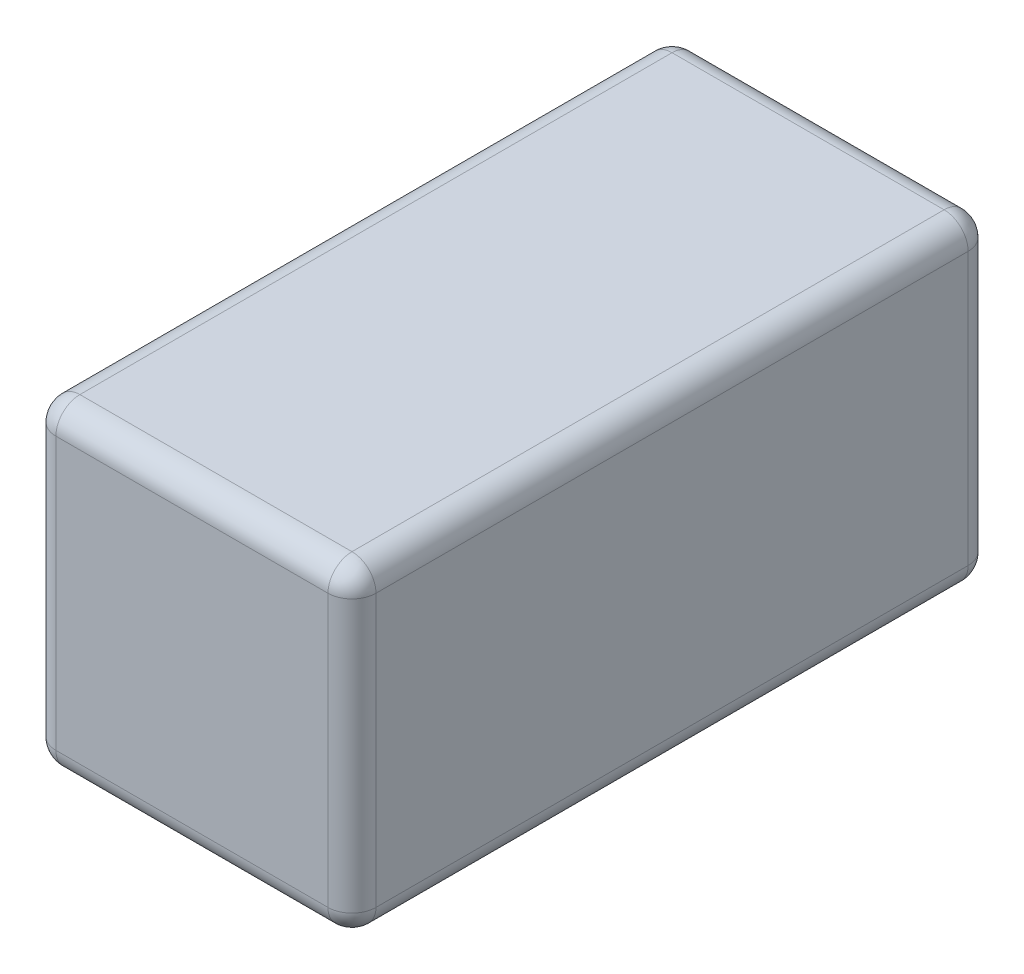
SolidWorks part; units mm, degrees
ref_plane "前视基准面" through (0, 0, 0) normal (0, 0, 1) x (1, 0, 0)
ref_plane "上视基准面" through (0, 0, 0) normal (0, 1, 0) x (1, 0, 0)
ref_plane "右视基准面" through (0, 0, 0) normal (1, 0, 0) x (0, 0, -1)
sketch "草图1" plane through (0, 0, 0) normal (0, 0, 1) x (1, 0, 0)
  line L1 (0, 0) -> (4, 0)
  line L2 (0, 0) -> (0, 4)
  line L3 (0, 4) -> (4, 4)
  line L4 (4, 0) -> (4, 4)
extrude "凸台-拉伸1" add sketch "草图1" along normal blind 8
fillet "圆角2" radius 0.3 1 edges at (2, 0, 0)
fillet "圆角3" radius 0.3 3 edges at (4, 0, 4.15) (4, 0.0879, 0.0879) (4, 2.15, 0)
fillet "圆角4" radius 0.3 3 edges at (0, 0, 4.15) (0, 0.0879, 0.0879) (0, 2.15, 0)
fillet "圆角5" radius 0.3 5 edges at (4, 4, 4.15) (3.9121, 4, 0.0879) (2, 4, 0) (0.0879, 4, 0.0879) (0, 4, 4.15)
fillet "圆角6" radius 0.3 8 edges at (0.0879, 3.9121, 8) (2, 4, 8) (3.9121, 3.9121, 8) (4, 2, 8) (3.9121, 0.0879, 8) (2, 0, 8) (0.0879, 0.0879, 8) (0, 2, 8)
